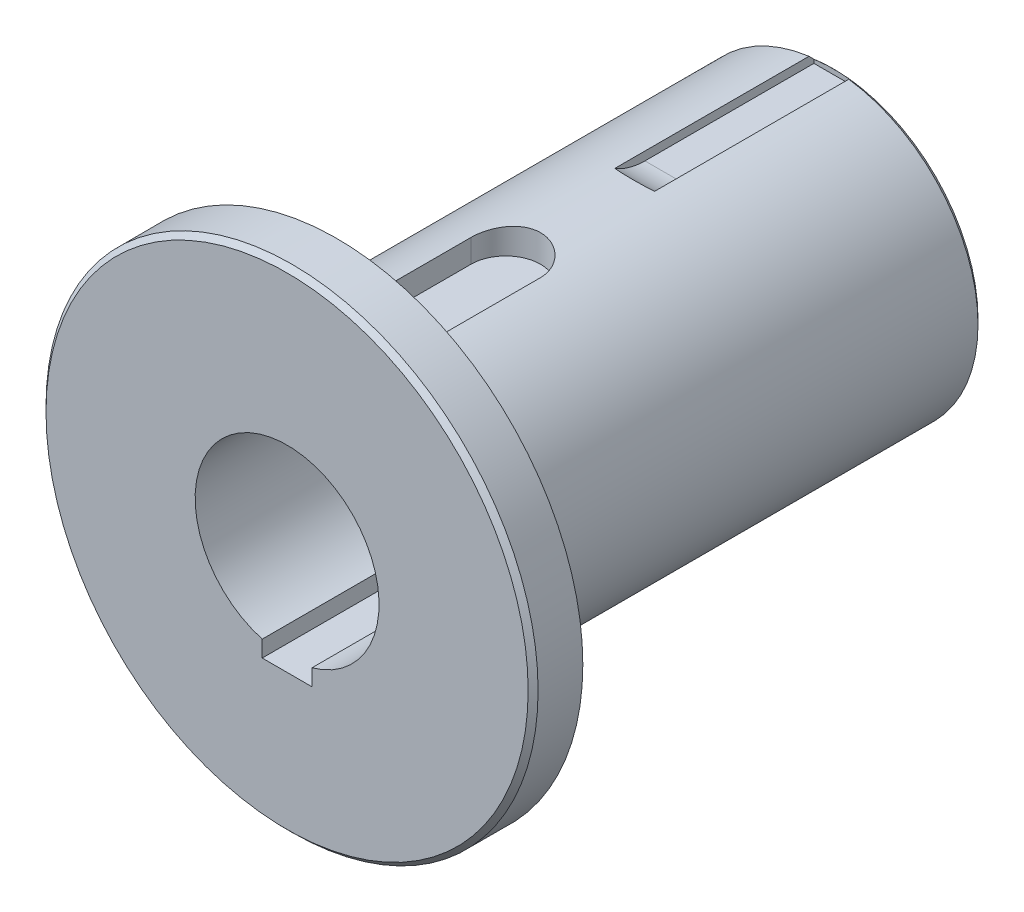
SolidWorks part; units mm, degrees
ref_plane "Piano frontale" through (0, 0, 0) normal (0, 0, 1) x (1, 0, 0)
ref_plane "Piano superiore" through (0, 0, 0) normal (0, 1, 0) x (1, 0, 0)
ref_plane "Piano destro" through (0, 0, 0) normal (1, 0, 0) x (0, 0, -1)
sketch "Schizzo1" plane through (0, 0, 0) normal (1, 0, 0) x (0, 0, -1)
  line L0 (-49.5662, 49.5) -> (-39.5662, 49.5)
  line L1 (-39.5662, 49.5) -> (-39.5662, 30)
  line L2 (-39.5662, 30) -> (60.4338, 30)
  line L3 (60.4338, 30) -> (60.4338, 18.5)
  line L4 (60.4338, 18.5) -> (-49.5662, 18.5)
  line L5 (-49.5662, 18.5) -> (-49.5662, 49.5)
  line L6 (-106.6152, 0) -> (181.0402, 0) construction
  point P10 (-39.5662, 39.75)
  point P11 (60.4338, 24.25)
  dimension "D1" = 99
  dimension "D2" = 18.5
  dimension "D3" = 10
  dimension "D4" = 11.5
  dimension "D5" = 100
revolve "Rivoluzione1" add sketch "Schizzo1" angle 360 about L6
sketch "Schizzo2" plane through (0, 0, -60.4338) normal (0, 0, -1) x (-1, 0, 0)
  line L0 (-5, -17.8115) -> (-5, -21.1115)
  line L1 (0, 0) -> (0, -34.8607) construction
  line L2 (-5, -21.1115) -> (5, -21.1115)
  line L3 (5, -17.8115) -> (5, -21.1115)
  circle A0 centre (0, 0) radius 18.5 construction
  point P9 (0, -21.1115)
  circle M5 centre (0, 0) radius 18.5
  dimension "D1" = 10
  dimension "D2" = 3.3
extrude "Taglio-Estrusione1" cut sketch "Schizzo2" against normal through all contours L1 L0 L2 M5 | L1 L2 L3 M5
ref_plane "Piano1" through (0, 30, 0) normal (0, -1, 0) x (-1, 0, 0)
sketch "Schizzo5" plane through (0, 30, 0) normal (0, -1, 0) x (-1, 0, 0)
  line L0 (0, -5.5662) -> (0, -27.5662) construction
  line L4 (7, -5.5662) -> (7, -27.5662)
  line L5 (-7, -5.5662) -> (-7, -27.5662)
  line L6 (18.5, 60.4338) -> (-18.5, 60.4338) construction
  arc A2 (7, -5.5662) -> (-7, -5.5662) centre (0, -5.5662) ccw
  arc A3 (-7, -27.5662) -> (7, -27.5662) centre (0, -27.5662) ccw
  point P2 (0, -16.5662)
  dimension "D1" = 66
  dimension "D2" = 22
  dimension "D3" = 14
extrude "Taglio-Estrusione5" cut sketch "Schizzo5" along normal blind 5.5
chamfer "Smusso1" distance 1 angle 45 2 edges at (30, 0, -60.4338) (49.5, 0, 49.5662)
cosmetic thread "Filettatura cosmetica5" parameters "D1"=45, "D2"=53.971
sketch "Schizzo7" plane through (0, 0, 0) normal (1, 0, 0) x (0, 0, -1)
  line L0 (26.4338, 39.5) -> (68.2521, 39.5) construction
  line L1 (26.4338, 51) -> (60.1902, 51)
  line L2 (26.4338, 28) -> (60.4225, 28)
  line L3 (60.4338, -29) -> (60.4338, 29) construction
  line L4 (59.4338, 30) -> (1.4337, 30) construction
  line L5 (60.1902, 51) -> (60.4225, 28)
  arc A0 (26.4338, 51) -> (26.4338, 28) centre (26.4338, 39.5) ccw
  point P2 (47.343, 39.5)
  dimension "D3" = 11.5
  dimension "D1" = 34
  dimension "D2" = 9.5
extrude "Taglio-Estrusione6" cut sketch "Schizzo7" against normal mid plane 8
